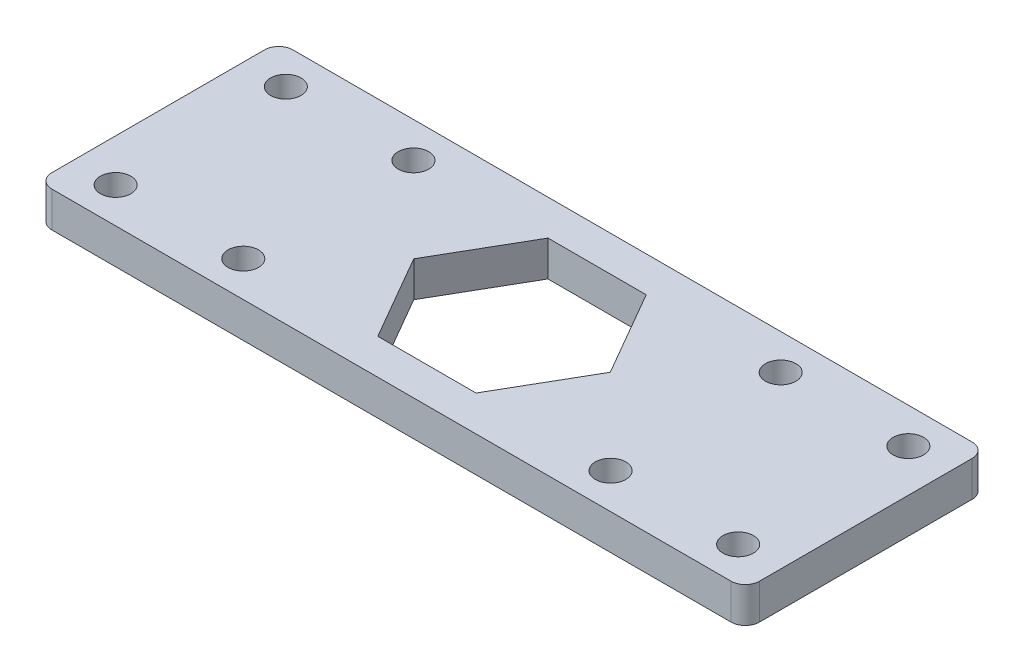
SolidWorks part; units mm, degrees
ref_plane "Front Plane" through (0, 0, 0) normal (0, 0, 1) x (1, 0, 0)
ref_plane "Top Plane" through (0, 0, 0) normal (0, 1, 0) x (1, 0, 0)
ref_plane "Right Plane" through (0, 0, 0) normal (1, 0, 0) x (0, 0, -1)
sketch "Sketch1" plane through (0, 0, 0) normal (0, 1, 0) x (1, 0, 0)
  line L1 (49.9, 17) -> (-49.9, 17)
  line L2 (49.9, 17) -> (49.9, -17)
  line L3 (49.9, -17) -> (-49.9, -17)
  line L4 (-49.9, 17) -> (-49.9, -17)
  line L5 (49.9, 17) -> (-49.9, -17) construction
  line L6 (49.9, -17) -> (-49.9, 17) construction
  point P0 (0, 0)
  dimension "D1" = 99.8
  dimension "D2" = 34
extrude "Boss-Extrude1" add sketch "Sketch1" along normal blind 5
sketch "Sketch2" plane through (0, 5, 0) normal (0, 1, 0) x (1, 0, 0)
  line L0 (-49.9, -17) -> (49.9, -17) construction
  line L2 (-49.9, 17) -> (-49.9, -17) construction
  line L3 (0, 17) -> (0, -17) construction
  line L4 (49.9, 17) -> (-49.9, 17) construction
  line L6 (-13.8564, 0) -> (-6.9282, -12)
  line L7 (-6.9282, -12) -> (6.9282, -12)
  line L8 (6.9282, -12) -> (13.8564, 0)
  line L9 (13.8564, 0) -> (6.9282, 12)
  line L10 (6.9282, 12) -> (-6.9282, 12)
  line L11 (-6.9282, 12) -> (-13.8564, 0)
  circle A0 centre (-43.9, 12) radius 2.15
  circle A1 centre (-25.9, 12) radius 2.15
  circle A2 centre (-43.9, -12) radius 2.15
  circle A3 centre (-25.9, -12) radius 2.15
  circle A4 centre (25.9, -12) radius 2.15
  circle A5 centre (43.9, -12) radius 2.15
  circle A6 centre (25.9, 12) radius 2.15
  circle A7 centre (43.9, 12) radius 2.15
  circle A8 centre (0, 0) radius 12 construction
  dimension "D1" = 4.3
  dimension "D2" = 24
  dimension "D3" = 18
  dimension "D4" = 5
  dimension "D5" = 6
  dimension "D6" = 5
extrude "Cut-Extrude1" cut sketch "Sketch2" against normal blind 5
fillet "Fillet1" radius 2 4 edges at (49.9, 2.5, -17) (49.9, 2.5, 17) (-49.9, 2.5, 17) (-49.9, 2.5, -17)
